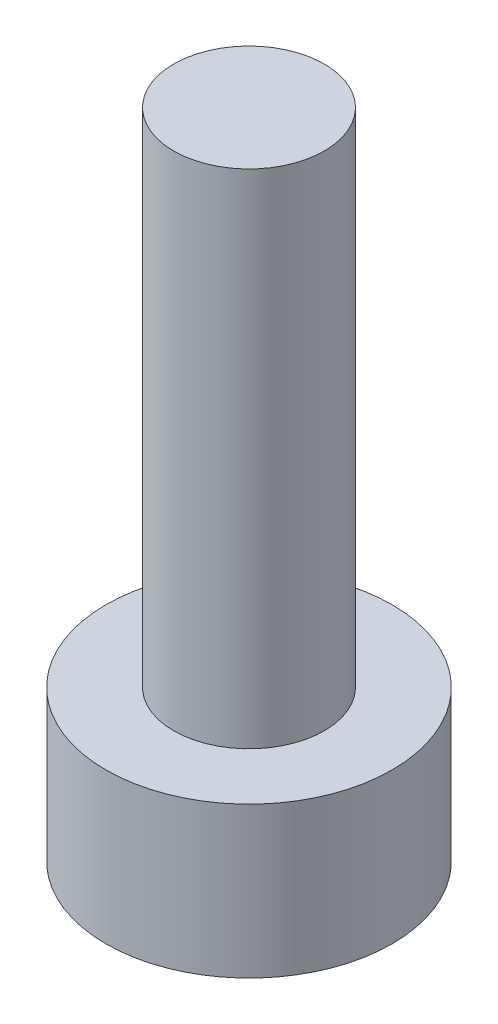
SolidWorks part; units mm, degrees
material "AISI 304"
ref_plane "前视基准面" through (0, 0, 0) normal (0, 0, 1) x (1, 0, 0)
ref_plane "上视基准面" through (0, 0, 0) normal (0, 1, 0) x (1, 0, 0)
ref_plane "右视基准面" through (0, 0, 0) normal (1, 0, 0) x (0, 0, -1)
sketch "草图1" plane through (0, 0, 0) normal (0, 0, 1) x (1, 0, 0)
  line L0 (0, 5.0793) -> (0, -4.5921) construction
  line L1 (-4.7636, 0) -> (5.5214, 0) construction
  line L2 (0, 0) -> (2.85, 0)
  line L3 (2.85, 0) -> (2.85, 3)
  line L4 (2.85, 3) -> (1.5, 3)
  line L5 (1.5, 3) -> (1.5, 13)
  line L6 (1.5, 13) -> (0, 13)
  line L7 (0, 13) -> (0, 0)
  dimension "D1" = 3
  dimension "D2" = 5.7
  dimension "D3" = 3
  dimension "D4" = 10
revolve "旋转1" add sketch "草图1" angle 360 about L0
sketch "草图2" plane through (0, 0, 0) normal (0, -1, 0) x (1, 0, 0)
  line L1 (0, -1.425) -> (1.2341, -0.7125)
  line L2 (1.2341, -0.7125) -> (1.2341, 0.7125)
  line L3 (1.2341, 0.7125) -> (0, 1.425)
  line L4 (0, 1.425) -> (-1.2341, 0.7125)
  line L5 (-1.2341, 0.7125) -> (-1.2341, -0.7125)
  line L6 (-1.2341, -0.7125) -> (0, -1.425)
  circle A0 centre (0, 0) radius 1.425 construction
  dimension "D1" = 2.85
extrude "切除-拉伸1" cut sketch "草图2" against normal blind 1.5
move or copy body "实体-移动/复制1" [suppressed] bodies to move or copy 107
equation "\"长度\"= 10"
equation "\"螺钉头直径\"= 5.7"
equation "\"螺钉直径\"= 3"
equation "\"螺钉头厚度\"= 3"
equation "\"D1@草图1\"= \"螺钉直径\""
equation "\"D2@草图1\"= \"螺钉头直径\""
equation "\"D3@草图1\"= \"螺钉头厚度\""
equation "\"D4@草图1\"= \"长度\""
equation "\"D1@草图2\"= \"螺钉头直径\" * 0.5"
